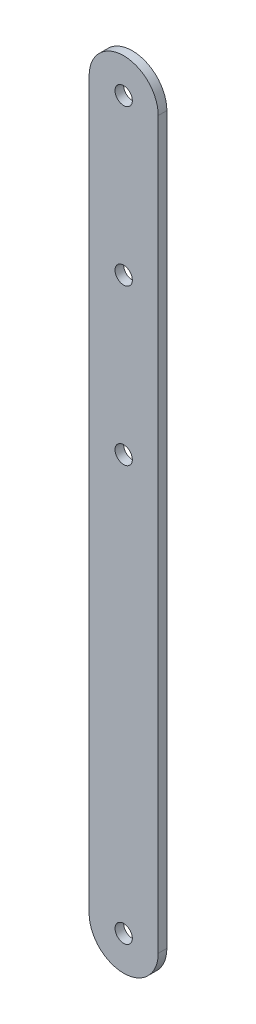
SolidWorks part; units mm, degrees
material "5052-H32"
ref_plane "Front Plane" through (0, 0, 0) normal (0, 0, 1) x (1, 0, 0)
ref_plane "Top Plane" through (0, 0, 0) normal (0, 1, 0) x (1, 0, 0)
ref_plane "Right Plane" through (0, 0, 0) normal (1, 0, 0) x (0, 0, -1)
sketch "Sketch1" plane through (0, 0, 0) normal (0, 0, 1) x (1, 0, 0)
  line L0 (-50.8, -1066.8) -> (-50.8, 0)
  line L1 (50.8, 0) -> (50.8, -1066.8)
  line L2 (0, -457.2) -> (0, -228.6) construction
  line L3 (0, 0) -> (0, -228.6) construction
  arc A0 (50.8, 0) -> (-50.8, 0) centre (0, 0) ccw
  arc A1 (-50.8, -1066.8) -> (50.8, -1066.8) centre (0, -1066.8) ccw
  circle A2 centre (0, 0) radius 12.7
  circle A3 centre (0, -1066.8) radius 12.7
  circle A5 centre (0, -228.6) radius 12.7
  circle A6 centre (0, -457.2) radius 12.7
  dimension "D1" = 50.8
  dimension "D3" = 25.4
  dimension "D4" = 25.4
  dimension "D5" = 228.6
  dimension "D2" = 1066.8
  dimension "D6" = 228.6
extrude "Boss-Extrude1" add sketch "Sketch1" along normal blind 12.7
sketch "Sketch2" plane through (0, 0, 12.7) normal (0, 0, 1) x (1, 0, 0)
  line L0 (0, -1066.8) -> (-381, -1726.7114) construction
  line L1 (0, -1066.8) -> (0, -939.8) construction
  line L2 (0, -939.8) -> (-437.0652, -1563.9939) construction
  line L3 (0, -812.8) -> (-489.8042, -1396.5259) construction
  line L4 (0, -685.8) -> (-538.8154, -1224.6154) construction
  line L5 (0, -558.8) -> (-583.7259, -1048.6042) construction
  line L6 (0, -431.8) -> (-624.1939, -868.8652) construction
  line L7 (0, -939.8) -> (0, -812.8) construction
  line L8 (0, -812.8) -> (0, -685.8) construction
  line L9 (0, -685.8) -> (0, -558.8) construction
  line L10 (0, -558.8) -> (0, -431.8) construction
  point P3 (-310.8782, -1591.1729)
  point P13 (-466.9807, -951.3218)
  point P14 (-466.9807, -843.6283)
  dimension "D1" = 762
  dimension "D2" = 150
  dimension "D3" = 5
  dimension "D4" = 127
  dimension "D5" = 5
  dimension "D6" = 5
  dimension "D7" = 5
  dimension "D8" = 5
